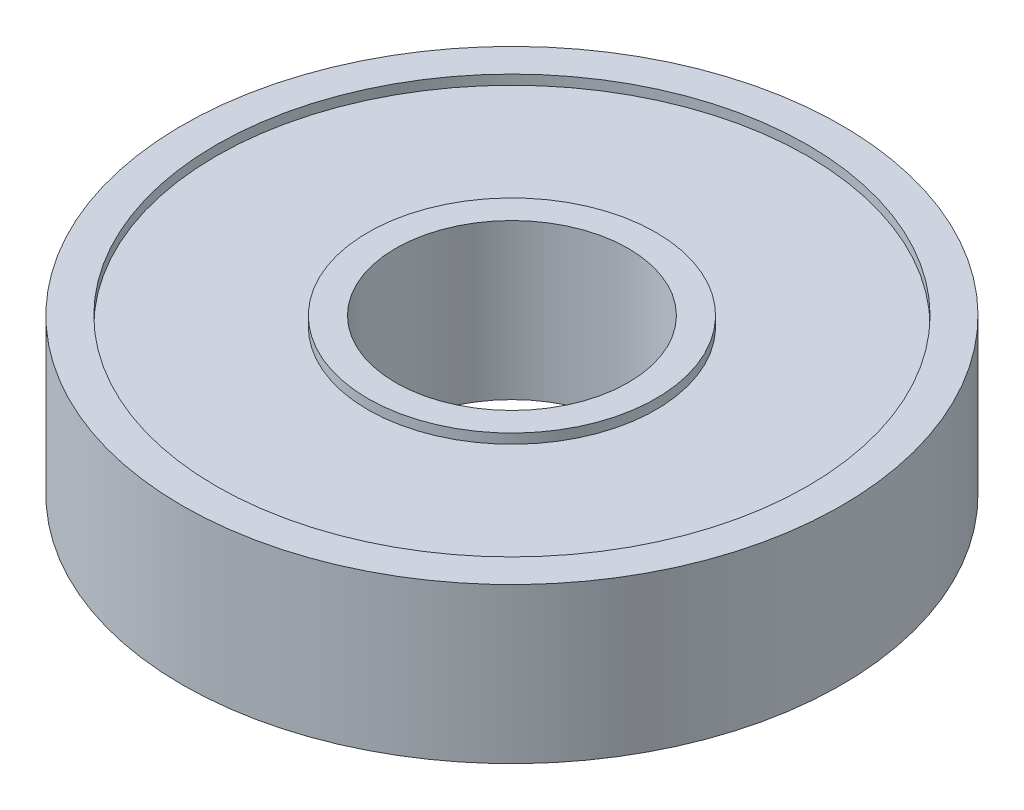
SolidWorks part; units mm, degrees
ref_plane "Спереди" through (0, 0, 0) normal (0, 0, 1) x (1, 0, 0)
ref_plane "Сверху" through (0, 0, 0) normal (0, 1, 0) x (1, 0, 0)
ref_plane "Справа" through (0, 0, 0) normal (1, 0, 0) x (0, 0, -1)
sketch "Эскиз1" plane through (0, 0, 0) normal (0, 1, 0) x (1, 0, 0)
  circle A0 centre (0, 0) radius 6
  circle A1 centre (0, 0) radius 17
extrude "Вытянуть1" add sketch "Эскиз1" along normal blind 8
sketch "Эскиз2" plane through (0, 8, 0) normal (0, 1, 0) x (1, 0, 0)
  circle A0 centre (0, 0) radius 7.4274
  circle A1 centre (0, 0) radius 15.2519
extrude "Вытянуть2" cut sketch "Эскиз2" against normal blind 0.5
sketch "Эскиз3" plane through (0, 0, 0) normal (0, -1, 0) x (1, 0, 0)
  circle A0 centre (0, 0) radius 7.4274
  circle A1 centre (0, 0) radius 15.2519
extrude "Вытянуть3" cut sketch "Эскиз3" against normal blind 0.5
